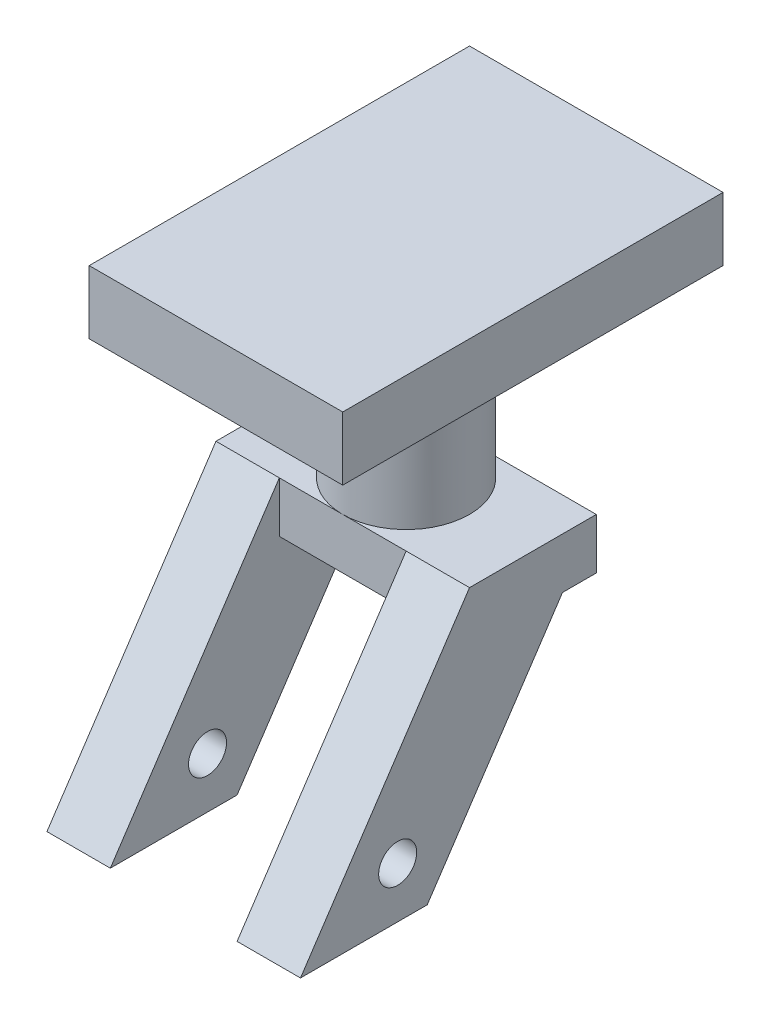
SolidWorks part; units mm, degrees
ref_plane "Front Plane" through (0, 0, 0) normal (0, 0, 1) x (1, 0, 0)
ref_plane "Top Plane" through (0, 0, 0) normal (0, 1, 0) x (1, 0, 0)
ref_plane "Right Plane" through (0, 0, 0) normal (1, 0, 0) x (0, 0, -1)
sketch "Sketch4" plane through (0, 0, 0) normal (0, 1, 0) x (1, 0, 0)
  line L1 (-5, 7.5) -> (5, 7.5)
  line L2 (-5, 7.5) -> (-5, -7.5)
  line L3 (-5, -7.5) -> (5, -7.5)
  line L4 (5, 7.5) -> (5, -7.5)
  line L5 (-5, 7.5) -> (5, -7.5) construction
  line L6 (-5, -7.5) -> (5, 7.5) construction
  point P0 (0, 0)
  dimension "D1" = 10
  dimension "D2" = 15
extrude "Boss-Extrude3" add sketch "Sketch4" along normal blind 2.5
sketch "Sketch5" plane through (0, 0, 0) normal (0, -1, 0) x (1, 0, 0)
  circle A0 centre (0, 0) radius 2.5
  dimension "D1" = 5
extrude "Boss-Extrude4" add sketch "Sketch5" along normal blind 6
sketch "Sketch6" plane through (0, -6, 0) normal (0, -1, 0) x (1, 0, 0)
  line L1 (-5, 2.5) -> (5, 2.5)
  line L2 (-5, 2.5) -> (-5, -2.5)
  line L3 (-5, -2.5) -> (5, -2.5)
  line L4 (5, 2.5) -> (5, -2.5)
  line L5 (-5, 2.5) -> (5, -2.5) construction
  line L6 (-5, -2.5) -> (5, 2.5) construction
  point P0 (0, 0)
  dimension "D1" = 10
  dimension "D2" = 5
extrude "Boss-Extrude5" add sketch "Sketch6" along normal blind 2
sketch "Sketch7" plane through (-5, 0, 0) normal (-1, 0, 0) x (0, 0, 1)
  line L0 (-2.5, -6) -> (2.5, -6)
  line L2 (4.1667, -16) -> (9.1667, -16)
  line L3 (9.1667, -16) -> (2.5, -6)
  line L4 (-2.5, -6) -> (4.1667, -16)
  dimension "D1" = 236.31
  dimension "D2" = 10
  dimension "D3" = 123.69
extrude "Boss-Extrude6" add sketch "Sketch7" against normal blind 2.5
sketch "Sketch8" plane through (5, 0, 0) normal (1, 0, 0) x (0, 0, -1)
  line L0 (2.5, -6) -> (-2.5, -6)
  line L1 (-2.5, -6) -> (-9.1667, -16)
  line L2 (-9.1667, -16) -> (-4.1667, -16)
  line L3 (-4.1667, -16) -> (2.5, -6)
extrude "Boss-Extrude7" add sketch "Sketch8" against normal blind 2.5
sketch "Sketch9" plane through (-5, 0, 0) normal (-1, 0, 0) x (0, 0, 1)
  line L0 (9.1667, -16) -> (2.5, -6) construction
  line L3 (4.1667, -16) -> (9.1667, -16) construction
  circle A0 centre (5.3333, -14) radius 0.75
  point P5 (6.6667, -16)
  dimension "D1" = 2.0801
  dimension "D2" = 2
extrude "Cut-Extrude1" cut sketch "Sketch9" against normal through all
